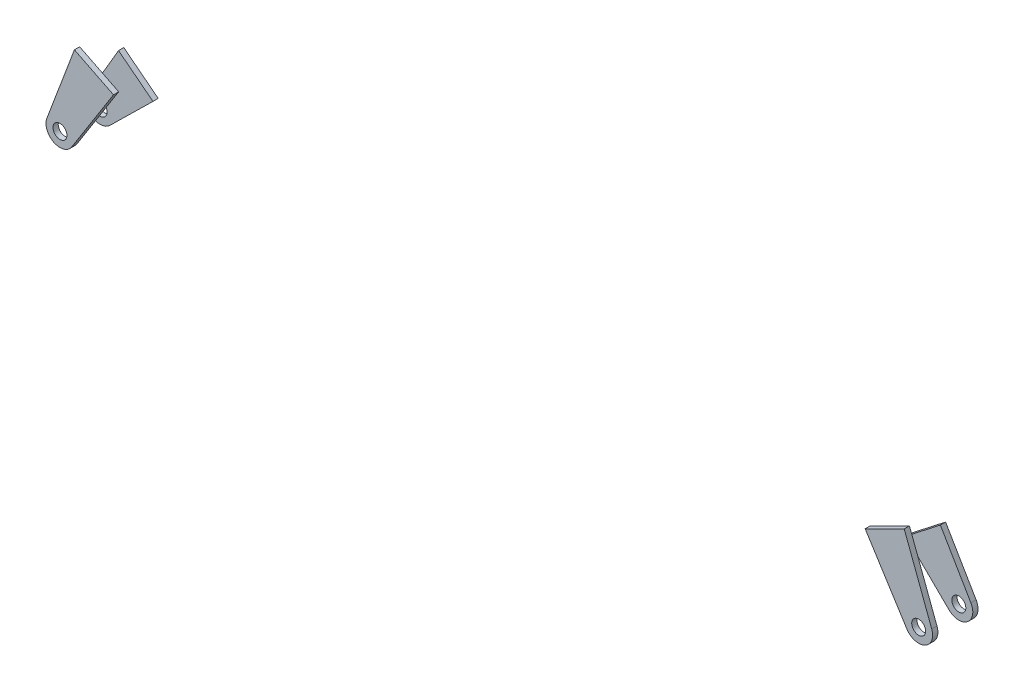
SolidWorks part; units mm, degrees
ref_plane "Front Plane" through (0, 0, 0) normal (0, 0, 1) x (1, 0, 0)
ref_plane "Top Plane" through (0, 0, 0) normal (0, 1, 0) x (1, 0, 0)
ref_plane "Right Plane" through (0, 0, 0) normal (1, 0, 0) x (0, 0, -1)
sketch3d "3DSketch1"
  line L0 (230, -2115, 305) -> (220, -2250, 95) construction
  line L1 (230, -2115, 305) -> (220, -2250, 95)
  line L2 (246, -2201, 222) -> (246, -2201, 232) construction
  line L3 (239.2399, -2205.2779, 232) -> (215.3367, -2167.5051, 232)
  line L4 (215.3367, -2167.5051, 232) -> (237.711, -2156.352, 232)
  line L5 (237.711, -2156.352, 232) -> (253.4853, -2198.1769, 232)
  circle A0 centre (246, -2201, 232) radius 4
  arc A1 (239.2399, -2205.2779, 232) -> (253.4853, -2198.1769, 232) centre (246, -2201, 232) ccw
  point P0 (246, -2201, 222)
  point P9 (246, -2201, 236)
  point P12 (246, -2201, 240)
  point P16 (226.5238, -2161.9286, 232)
  point P17 (0, 0, 0)
  point P18 (0, 0, 0)
  point P19 (0, 0, 0)
  dimension "D1" = 8
  dimension "D3" = 25
  dimension "D2" = 4
extrude "Boss-Extrude-U" add sketch "3DSketch1" along a picked direction on the side of the normal blind 3 contours L5 A1 L3 L4 | A0
sketch3d "3DSketch2"
  line L0 (230, -2115, 305) -> (220, -2250, 95) construction
  line L1 (230, -2115, 305) -> (220, -2250, 95) construction
  line L2 (246, -2201, 222) -> (246, -2201, 212) construction
  line L3 (240.3947, -2206.708, 212) -> (215.7118, -2182.4693, 212)
  line L4 (215.7118, -2182.4693, 212) -> (235.4311, -2167.1022, 212)
  line L5 (235.4311, -2167.1022, 212) -> (252.9045, -2196.9592, 212)
  circle A0 centre (246, -2201, 212) radius 4
  arc A1 (240.3947, -2206.708, 212) -> (252.9045, -2196.9592, 212) centre (246, -2201, 212) ccw
  point P0 (246, -2201, 222)
  point P9 (246, -2201, 216)
  point P12 (246, -2201, 220)
  point P16 (283.2237, -2248.7661, 212)
  point P17 (283.2237, -2248.7661, 212)
  point P18 (225.5714, -2174.7857, 212)
  point P19 (0, 0, 0)
  dimension "D1" = 8
  dimension "D2" = 4
  dimension "D3" = 25
extrude "Boss-Extrude-L" add sketch "3DSketch2" along a picked direction on the side against the normal blind 3
mirror "Mirror1" about plane through (0, 0, 0) normal (1, 0, 0) of bodies 111 112
